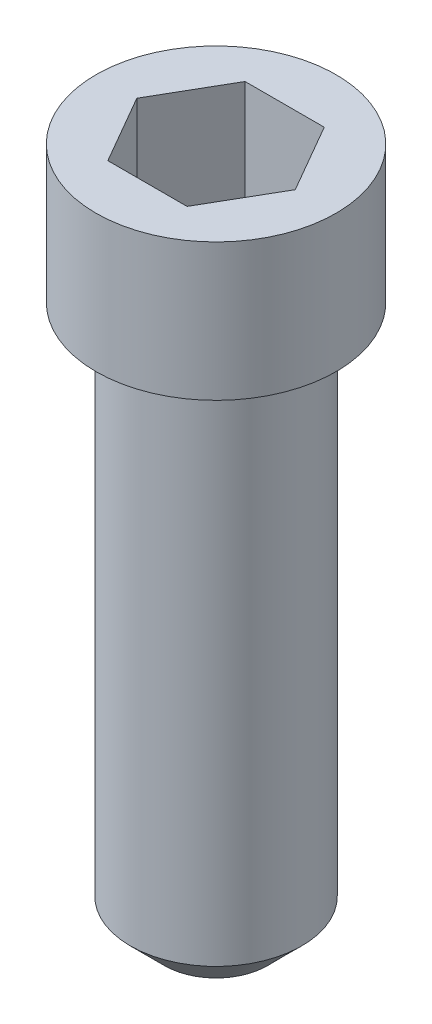
SolidWorks part; units mm, degrees
material "Plain Carbon Steel"
ref_plane "Front Plane" through (0, 0, 0) normal (0, 0, 1) x (1, 0, 0)
ref_plane "Top Plane" through (0, 0, 0) normal (0, 1, 0) x (1, 0, 0)
ref_plane "Right Plane" through (0, 0, 0) normal (1, 0, 0) x (0, 0, -1)
sketch "Sketch1" plane through (0, 0, 0) normal (0, 1, 0) x (1, 0, 0)
  circle A0 centre (0, 0) radius 2.5
  dimension "D1" = 5
extrude "Boss-Extrude1" add sketch "Sketch1" along normal blind 16
sketch "Sketch2" plane through (0, 16, 0) normal (0, 1, 0) x (1, 0, 0)
  circle A0 centre (0, 0) radius 3.5
  dimension "D1" = 7
extrude "Boss-Extrude2" add sketch "Sketch2" along normal blind 4
chamfer "Chamfer1" distance 1 angle 45 1 edges at (0, 0, 2.5)
sketch "Sketch3" plane through (0, 20, 0) normal (0, 1, 0) x (1, 0, 0)
  line L1 (2.3094, 0) -> (1.1547, 2)
  line L2 (1.1547, 2) -> (-1.1547, 2)
  line L3 (-1.1547, 2) -> (-2.3094, 0)
  line L4 (-2.3094, 0) -> (-1.1547, -2)
  line L5 (-1.1547, -2) -> (1.1547, -2)
  line L6 (1.1547, -2) -> (2.3094, 0)
  circle A0 centre (0, 0) radius 2 construction
  dimension "D1" = 4
extrude "Cut-Extrude1" cut sketch "Sketch3" against normal blind 3
